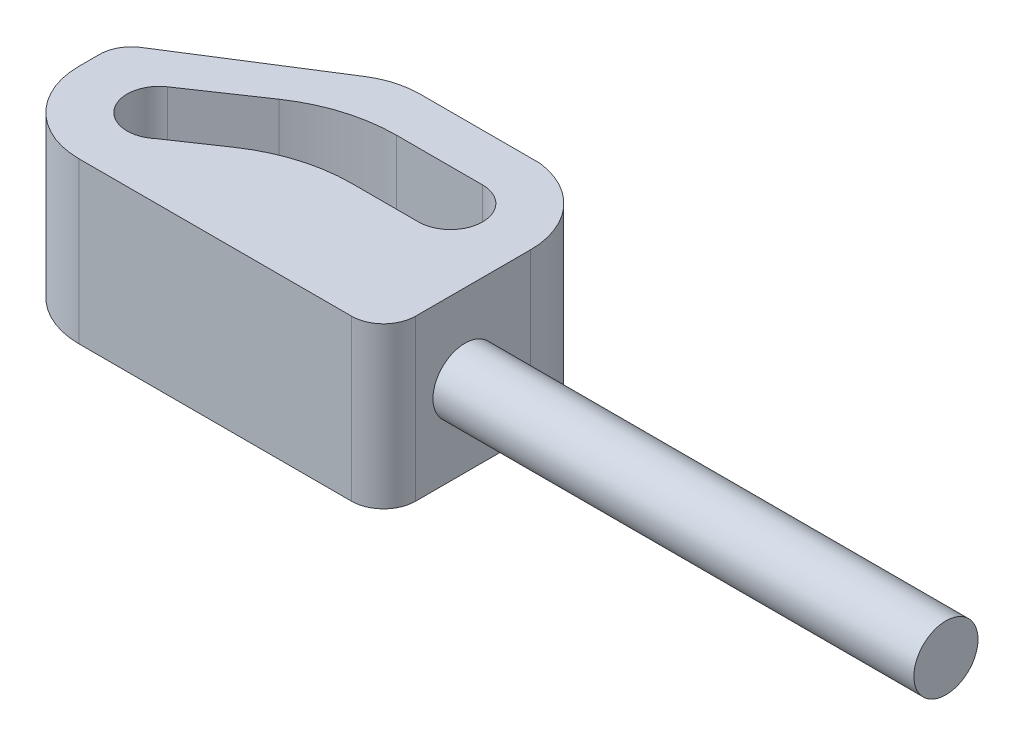
SolidWorks part; units mm, degrees
ref_plane "Front Plane" through (0, 0, 0) normal (0, 0, 1) x (1, 0, 0)
ref_plane "Top Plane" through (0, 0, 0) normal (0, 1, 0) x (1, 0, 0)
ref_plane "Right Plane" through (0, 0, 0) normal (1, 0, 0) x (0, 0, -1)
sketch "Sketch1" plane through (0, 0, 0) normal (0, 1, 0) x (1, 0, 0)
  line L1 (-4.9157, -9.9157) -> (12.0843, -9.9157)
  line L2 (-9.9157, -4.9157) -> (-9.9157, -3.644)
  line L4 (14.0843, -7.9157) -> (14.0843, -0.7383)
  line L5 (-9.9157, -9.9157) -> (-6.3299, -6.3299) construction
  line L6 (-5.5423, 3.9019) -> (14.0843, -9.9157) construction
  line L8 (14.0843, -0.7383) -> (14.0843, -9.9157)
  line L9 (-6.0369, -3.2595) -> (-1.8984, -0.4576)
  line L10 (9.0843, 1.2617) -> (3.7079, 1.2617)
  line L11 (9.0843, -2.7383) -> (4.9089, -2.7383)
  line L12 (-0.6974, -4.4576) -> (-3.6041, -6.4256)
  line L13 (0, 0) -> (4.855, 4.855) construction
  line L14 (9.7303, 4.2198) -> (2.2244, 4.2198)
  line L15 (-0.4483, 3.4455) -> (-8.9848, -1.9537)
  arc A0 (-6.0369, -3.2595) -> (-3.6041, -6.4256) centre (-4.9157, -4.9157) ccw
  arc A1 (9.0843, -2.7383) -> (9.0843, 1.2617) centre (9.0843, -0.7383) ccw
  arc A2 (-0.6974, -4.4576) -> (4.9089, -2.7383) centre (4.9089, -12.7383) cw
  arc A3 (-1.8984, -0.4576) -> (3.7079, 1.2617) centre (3.7079, -8.7383) cw
  arc A5 (14.0843, -0.7383) -> (9.7303, 4.2198) centre (9.0843, -0.7383) ccw
  arc A7 (-9.9157, -4.9157) -> (-4.9157, -9.9157) centre (-4.9157, -4.9157) ccw
  arc A8 (2.2244, 4.2198) -> (-0.4483, 3.4455) centre (2.2244, -0.7802) ccw
  arc A9 (-8.9848, -1.9537) -> (-9.9157, -3.644) centre (-7.9157, -3.644) ccw
  arc A10 (12.0843, -9.9157) -> (14.0843, -7.9157) centre (12.0843, -7.9157) ccw
  point P0 (0, 0)
  dimension "D1" = 4
  dimension "D2" = 4
  dimension "D4" = 10
  dimension "D5" = 5
  dimension "D6" = 5
  dimension "D7" = 2
  dimension "D8" = 5
  dimension "D9" = 2
  dimension "D3" = 24
extrude "Boss-Extrude1" add sketch "Sketch1" along normal blind 10 contours A3 L9 A0 L12 A2 L11 A1 L10 | A5 L14 A8 L15 A9 L2 A7 L1 A10 L4
sketch "Sketch2" plane through (14.0843, 0, 0) normal (1, 0, 0) x (0, 0, -1)
  circle A0 centre (-4.8339, 5) radius 2
  dimension "D1" = 4
extrude "Boss-Extrude2" add sketch "Sketch2" along normal blind 30
sketch "Sketch3" plane through (0, 10, 0) normal (0, 1, 0) x (1, 0, 0)
  line L0 (-4.9157, -4.9157) -> (-1.2851, -2.4576)
  line L1 (4.3212, -0.7383) -> (9.0843, -0.7383)
  line L2 (-6.0369, -3.2595) -> (-1.8984, -0.4576) construction
  line L3 (9.0843, 1.2617) -> (3.7079, 1.2617) construction
  arc A0 (-1.2851, -2.4576) -> (4.3212, -0.7383) centre (4.3212, -10.7383) cw
  dimension "D1" = 10
